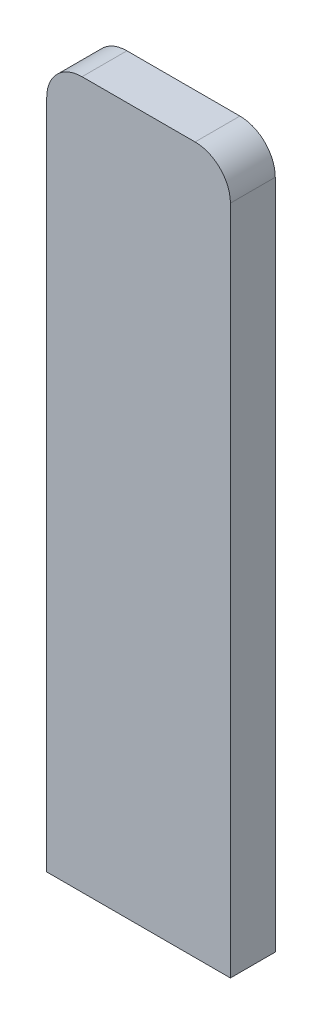
SolidWorks part; units mm, degrees
ref_plane "Front Plane" through (0, 0, 0) normal (0, 0, 1) x (1, 0, 0)
ref_plane "Top Plane" through (0, 0, 0) normal (0, 1, 0) x (1, 0, 0)
ref_plane "Right Plane" through (0, 0, 0) normal (1, 0, 0) x (0, 0, -1)
sketch "Sketch1" plane through (0, 0, 7.303) normal (0, 0, -1) x (-1, 0, 0)
  line L1 (1.3253, -21.2507) -> (27.3253, -21.2507)
  line L2 (1.3253, -21.2507) -> (1.3253, 73.7493)
  line L3 (6.3253, 78.7493) -> (22.3253, 78.7493)
  line L4 (27.3253, -21.2507) -> (27.3253, 73.7493)
  arc A0 (22.3253, 78.7493) -> (27.3253, 73.7493) centre (22.3253, 73.7493) cw
  arc A1 (1.3253, 73.7493) -> (6.3253, 78.7493) centre (6.3253, 73.7493) cw
  point P6 (27.3253, 78.7493)
  dimension "D3" = 5
  dimension "D4" = 5
  dimension "D1" = 100
  dimension "D2" = 26
extrude "Boss-Extrude1" add sketch "Sketch1" along normal blind 6.35
